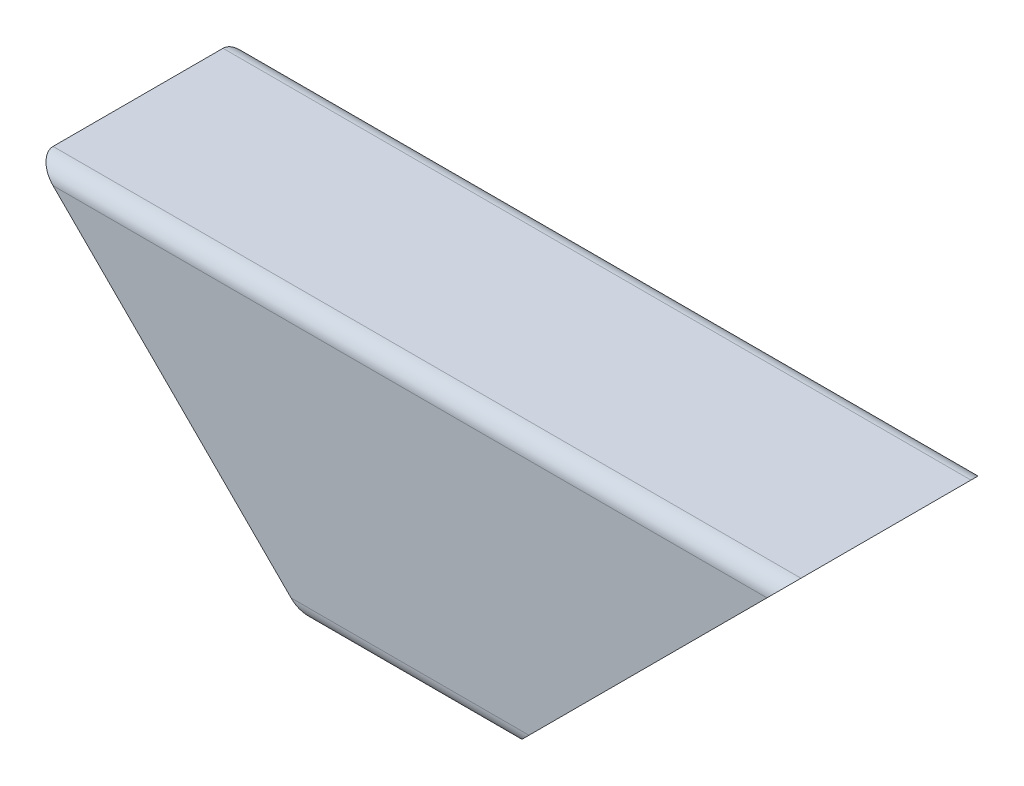
SolidWorks part; units mm, degrees
material "Plain Carbon Steel"
ref_plane "Front Plane" through (0, 0, 0) normal (0, 0, 1) x (1, 0, 0)
ref_plane "Top Plane" through (0, 0, 0) normal (0, 1, 0) x (1, 0, 0)
ref_plane "Right Plane" through (0, 0, 0) normal (1, 0, 0) x (0, 0, -1)
sketch "Sketch1" plane through (0, 0, 0) normal (1, 0, 0) x (0, 0, -1)
  line L1 (-71.6855, -13.3442) -> (-39.9355, -13.3442)
  line L2 (-74.8605, -10.1692) -> (-74.8605, 34.2808)
  line L3 (-71.6855, 37.4558) -> (-39.9355, 37.4558)
  line L4 (-36.7605, -10.1692) -> (-36.7605, 34.2808)
  arc A0 (-74.8605, 34.2808) -> (-71.6855, 37.4558) centre (-71.6855, 34.2808) cw
  arc A1 (-74.8605, -10.1692) -> (-71.6855, -13.3442) centre (-71.6855, -10.1692) ccw
  arc A2 (-39.9355, -13.3442) -> (-36.7605, -10.1692) centre (-39.9355, -10.1692) ccw
  arc A3 (-36.7605, 34.2808) -> (-39.9355, 37.4558) centre (-39.9355, 34.2808) ccw
  point P6 (-74.8605, 37.4558)
  point P11 (-36.7605, -13.3442)
  point P14 (-36.7605, 37.4558)
  dimension "D3" = 3.175
  dimension "D1" = 50.8
  dimension "D2" = 38.1
extrude "Extrude-Thin2" add sketch "Sketch1" along normal blind 139.7 thin thin type one direction reverse wall 1.651
sketch "Sketch3" plane through (0, 0, 74.8605) normal (0, 0, 1) x (1, 0, 0)
  line L0 (0, 37.4558) -> (0, -38.7442)
  line L1 (0, -38.7442) -> (76.2, -38.7442)
  line L2 (76.2, -38.7442) -> (0, 37.4558)
  line L3 (139.7, 37.4558) -> (81.28, -20.9642)
  line L4 (81.28, -20.9642) -> (139.7, -20.9642)
  line L5 (139.7, -20.9642) -> (139.7, 37.4558)
  dimension "D1" = 76.2
  dimension "D2" = 76.2
  dimension "D3" = 58.42
  dimension "D4" = 58.42
extrude "Cut-Extrude1" cut sketch "Sketch3" against normal through all
sketch "Sketch4" plane through (0, 0, 74.8605) normal (0, 0, 1) x (1, 0, 0)
  circle A0 centre (69.85, 24.7558) radius 4.7625
  dimension "D1" = 9.525
  dimension "D2" = 12.7
  dimension "D3" = 69.85
sketch "Sketch5" plane through (0, 0, 74.8605) normal (0, 0, 1) x (1, 0, 0)
  circle A0 centre (69.85, 24.7558) radius 4.7625
